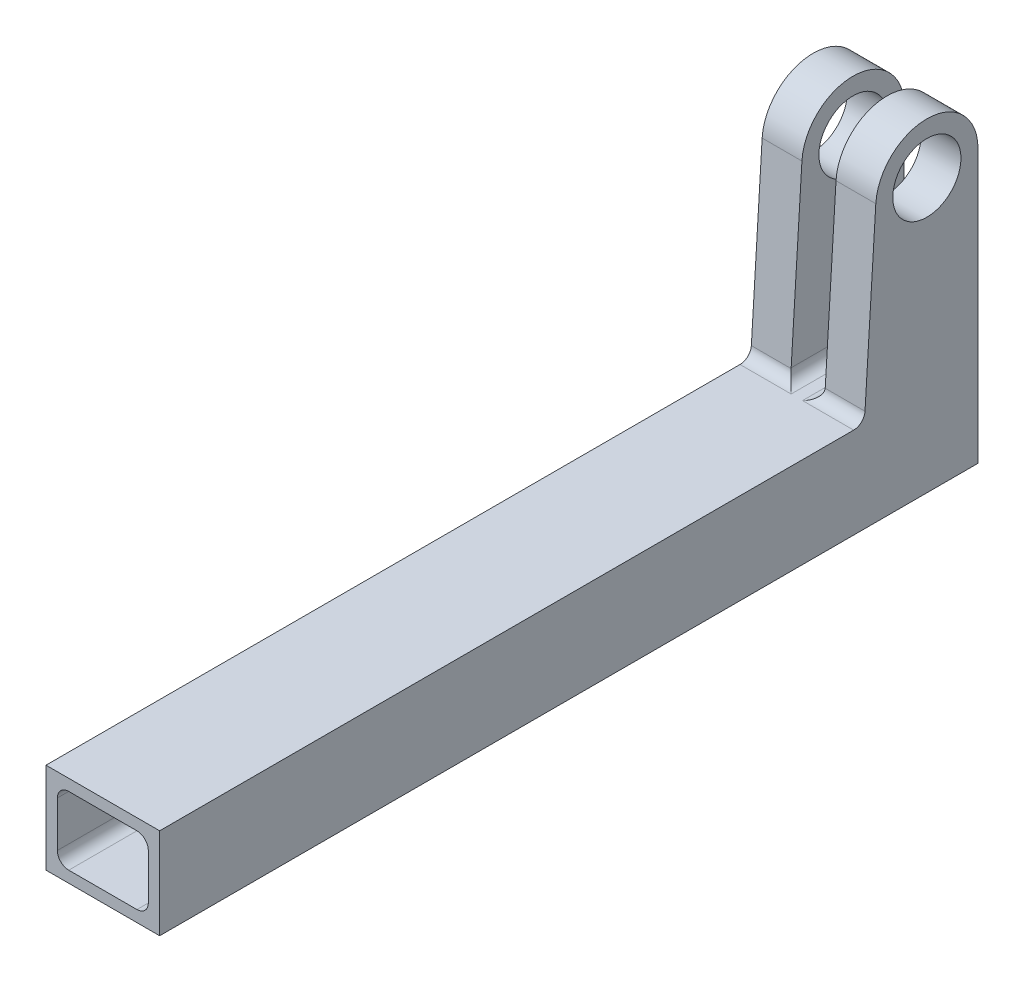
SolidWorks part; units mm, degrees
material "AISI 1045 Steel, cold drawn"
ref_plane "Front Plane" through (0, 0, 0) normal (0, 0, 1) x (1, 0, 0)
ref_plane "Top Plane" through (0, 0, 0) normal (0, 1, 0) x (1, 0, 0)
ref_plane "Right Plane" through (0, 0, 0) normal (1, 0, 0) x (0, 0, -1)
sketch "Sketch1" plane through (0, 0, 0) normal (1, 0, 0) x (0, 0, -1)
  line L0 (0, 0) -> (-914.4, 0)
  line L1 (-914.4, 0) -> (-914.4, 101.6)
  line L2 (-914.4, 101.6) -> (0, 101.6)
  line L3 (0, 101.6) -> (0, 0)
  line L4 (0, 101.6) -> (0, 304.8)
  line L5 (-114.1906, 308.3343) -> (-127, 101.6)
  arc A0 (0, 304.8) -> (-114.1906, 308.3343) centre (-57.15, 304.8) ccw
  circle A1 centre (-57.15, 304.8) radius 38.1
  point P8 (0, 0)
  point P10 (-122.5268, 50.8)
  point P11 (0, 0)
  dimension "D1" = 101.6
  dimension "D4" = 76.2
  dimension "D2" = 914.4
  dimension "D3" = 203.2
  dimension "D5" = 19.05
  dimension "D6" = 69.85
sketch "Sketch2" plane through (0, 0, 0) normal (0, 0, 1) x (1, 0, 0)
  line L0 (0, 101.6) -> (0, 0) construction
  line L1 (0, 101.6) -> (-127, 101.6)
  line L2 (0, 101.6) -> (0, 0)
  line L3 (0, 0) -> (-127, 0)
  line L4 (-127, 101.6) -> (-127, 0)
  line L5 (0, 101.6) -> (0, 304.8) construction
  line L6 (-12.7, 88.9) -> (-12.7, 12.7)
  line L7 (-12.7, 12.7) -> (-114.3, 12.7)
  line L8 (-114.3, 88.9) -> (-114.3, 12.7)
  line L9 (-12.7, 88.9) -> (-114.3, 88.9)
  point P8 (0, 0)
  dimension "D1" = 101.6
  dimension "D2" = 127
  dimension "D3" = 12.7
extrude "Boss-Extrude2" add sketch "Sketch2" along normal up to vertex (914.4 mm away) up to point (0, 101.6, 914.4)
extrude "Boss-Extrude3" add sketch "Sketch1" against normal blind 44.45 contours L4 A0 L5 L2 A1
ref_plane "Plane1" through (-127, 0, 0) normal (-1, 0, 0) x (0, 0, 1)
sketch "Sketch3" plane through (-127, 0, 0) normal (-1, 0, 0) x (0, 0, 1)
  line L3 (0, 304.8) -> (0, 101.6)
  line L4 (0, 101.6) -> (127, 101.6)
  line L5 (127, 101.6) -> (114.1906, 308.3343)
  line L6 (0, 304.8) -> (0, 101.6)
  line L7 (0, 101.6) -> (127, 101.6)
  line L8 (127, 101.6) -> (114.1906, 308.3343)
  circle A0 centre (57.15, 304.8) radius 38.1 construction
  arc A1 (114.1906, 308.3343) -> (0, 304.8) centre (57.15, 304.8) ccw
  arc A2 (114.1906, 308.3343) -> (0, 304.8) centre (57.15, 304.8) ccw
  circle A3 centre (57.15, 304.8) radius 38.1
  dimension "D1" = 0
extrude "Boss-Extrude5" add sketch "Sketch3" against normal blind 44.45
fillet "Fillet1" radius 12.7 4 edges at (-12.7, 12.7, 457.2) (-12.7, 88.9, 457.2) (-114.3, 88.9, 457.2) (-114.3, 12.7, 457.2)
fillet "Fillet2" radius 12.7 4 edges at (-104.775, 101.6, 127) (-22.225, 101.6, 127) (-82.55, 101.6, 63.5) (-44.45, 101.6, 63.5)
equation "\"D1@Sketch2\"=\"D1@Sketch1\""
